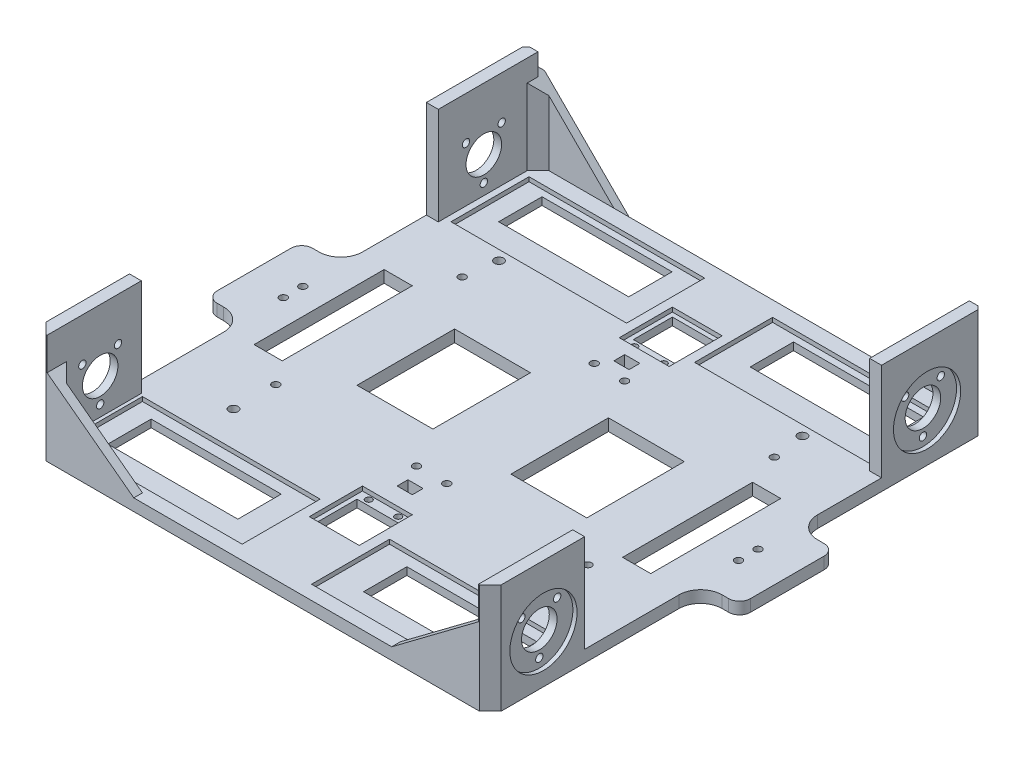
SolidWorks part; units mm, degrees
ref_plane "前视基准面" through (0, 0, 0) normal (0, 0, 1) x (1, 0, 0)
ref_plane "上视基准面" through (0, 0, 0) normal (0, 1, 0) x (1, 0, 0)
ref_plane "右视基准面" through (0, 0, 0) normal (1, 0, 0) x (0, 0, -1)
sketch "草图2" plane through (0, 0, 0) normal (0, 1, 0) x (1, 0, 0)
  line L1 (105, -109) -> (-105, -109)
  line L2 (130, -52) -> (130, 52)
  line L3 (105, 117.5) -> (-105, 117.5)
  line L4 (-130, -52) -> (-130, 52)
  line L5 (105, -94.9038) -> (-105, 94.9038) construction
  line L6 (105, 94.9038) -> (-105, -94.9038) construction
  line L9 (-130, 52) -> (-105, 52)
  line L10 (-105, 117.5) -> (-105, 52)
  line L13 (130, 52) -> (105, 52)
  line L14 (105, 117.5) -> (105, 52)
  line L17 (-130, -52) -> (-105, -52)
  line L18 (-105, -109) -> (-105, -52)
  line L21 (130, -52) -> (105, -52)
  line L22 (105, -109) -> (105, -52)
  line L23 (105, -109) -> (99.5, -109)
  line L24 (105, -109) -> (105, -74)
  line L25 (105, -74) -> (99.5, -74)
  line L26 (99.5, -109) -> (99.5, -74)
  line L27 (105, 117.5) -> (99.5, 117.5)
  line L28 (105, 117.5) -> (105, 82.5)
  line L29 (105, 82.5) -> (99.5, 82.5)
  line L30 (99.5, 117.5) -> (99.5, 82.5)
  point P0 (0, 0)
  dimension "D1" = 35
  dimension "D2" = 5.5
  dimension "D3" = 65.5
  dimension "D4" = 57
  dimension "D5" = 35
  dimension "D6" = 65.5
  dimension "D7" = 57
  dimension "D8" = 104
extrude "凸台-拉伸1" add sketch "草图2" along normal blind 5.5 contours L4 L9 L10 L3 L14 L13 L2 L21 L22 L1 L18 L17
sketch "草图5" plane through (0, 5.5, 0) normal (0, 1, 0) x (1, 0, 0)
  line L1 (105, -109) -> (99.5, -109)
  line L2 (105, -109) -> (105, -59.5)
  line L3 (105, -59.5) -> (99.5, -59.5)
  line L4 (99.5, -109) -> (99.5, -59.5)
  line L5 (105, 117.5) -> (99.5, 117.5)
  line L6 (105, 117.5) -> (105, 71.5)
  line L7 (105, 71.5) -> (99.5, 71.5)
  line L8 (99.5, 117.5) -> (99.5, 71.5)
extrude "凸台-拉伸2" add sketch "草图5" along normal blind 45
sketch "草图8" plane through (0, 0, -117.5) normal (0, 0, -1) x (-1, 0, 0)
  line L0 (-105, 45.921) -> (-59.079, 0)
  line L1 (-105, 50.5) -> (-105, 0) construction
  line L2 (-105, 0) -> (105, 0) construction
  line L3 (-59.079, 0) -> (-105, 0)
  line L4 (-105, 0) -> (-105, 45.921)
  dimension "D1" = 64.9422
  dimension "D2" = 45.921
  dimension "D3" = 45.921
extrude "凸台-拉伸4" add sketch "草图8" along normal blind 3.5
sketch "草图9" plane through (0, 5.5, 0) normal (0, 1, 0) x (1, 0, 0)
  line L0 (0, -109) -> (0, 117.5) construction
  line L3 (99.5, -109) -> (-105, -109) construction
  line L4 (64.579, 117.5) -> (-105, 117.5) construction
  circle A0 centre (-7, 50.9229) radius 1.7
  circle A1 centre (-71.9999, 55.0189) radius 1.7
  circle A2 centre (-71.9999, -30.9811) radius 1.7
  circle A3 centre (-7, -31.0771) radius 1.7
  circle A4 centre (7, -31.0771) radius 1.7
  circle A5 centre (71.9999, -30.9811) radius 1.7
  circle A6 centre (71.9999, 55.0189) radius 1.7
  circle A7 centre (7, 50.9229) radius 1.7
  dimension "D2" = 3.4
  dimension "D3" = 3.4
  dimension "D4" = 3.4
  dimension "D5" = 3.4
  dimension "D7" = 86
  dimension "D8" = 7
  dimension "D9" = 65
  dimension "D10" = 7
  dimension "D1" = 226.5
sketch "草图10" plane through (0, 5.5, 0) normal (0, 1, 0) x (1, 0, 0)
  line L1 (-105, 117.5) -> (-99.5, 117.5)
  line L2 (-105, 117.5) -> (-105, 71.5)
  line L3 (-105, 71.5) -> (-99.5, 71.5)
  line L4 (-99.5, 117.5) -> (-99.5, 71.5)
  line L5 (-105, -109) -> (-99.5, -109)
  line L6 (-105, -109) -> (-105, -59.5)
  line L7 (-105, -59.5) -> (-99.5, -59.5)
  line L8 (-99.5, -109) -> (-99.5, -59.5)
extrude "凸台-拉伸5" add sketch "草图10" along normal blind 45
sketch "草图11" plane through (0, 0, -117.5) normal (0, 0, -1) x (-1, 0, 0)
  line L0 (99.5, 50.5) -> (99.5, 5.5) construction
  line L1 (-64.579, 5.5) -> (99.5, 5.5) construction
  line L3 (-59.079, 0) -> (105, 0) construction
  line L4 (59, 0) -> (105, 46)
  line L6 (105, 46) -> (105, 0)
  line L7 (105, 50.5) -> (105, 0) construction
  line L8 (105, 0) -> (59, 0)
  point P0 (99.5, 40.5)
  point P5 (64.5, 5.5)
  dimension "D4" = 65.0538
  dimension "D5" = 46
  dimension "D6" = 46
extrude "凸台-拉伸6" add sketch "草图11" along normal blind 3.5 contours L4 L6 L8
sketch "草图15" plane through (0, 0, 109) normal (0, 0, 1) x (1, 0, 0)
  line L0 (-99.5, 40.5) -> (-59, 0)
  line L1 (105, 0) -> (-105, 0) construction
  line L2 (-59, 0) -> (-105, 46)
  point P8 (-105, 46)
  point P9 (-59, 0)
  dimension "D1" = 57.2756
  dimension "D2" = 65.0538
sketch "草图18" plane through (-105, 0, 0) normal (-1, 0, 0) x (0, 0, 1)
  line L0 (-117.5, 46) -> (-117.5, 5.5) construction
  line L1 (-71.5, 50.5) -> (-71.5, 5.5) construction
  line L2 (59.5, 50.5) -> (59.5, 5.5) construction
  line L4 (109, 5.5) -> (-117.5, 5.5) construction
  line L6 (109, 0) -> (52, 0) construction
  line L11 (52, 0) -> (109, 0)
  line L12 (109, 0) -> (109, 50.5)
  line L13 (109, 50.5) -> (59.5, 50.5)
  line L14 (59.5, 50.5) -> (59.5, 5.5)
  line L15 (59.5, 5.5) -> (52, 5.5)
  line L16 (52, 5.5) -> (52, 0)
  line L17 (52, 0) -> (109, 0)
  line L18 (109, 0) -> (109, 50.5)
  line L19 (109, 50.5) -> (59.5, 50.5)
  line L20 (59.5, 50.5) -> (59.5, 5.5)
  line L21 (59.5, 5.5) -> (52, 5.5)
  line L22 (52, 5.5) -> (52, 0)
  circle A1 centre (-92.5, 22) radius 8.2
  circle A3 centre (-100.725, 30.6) radius 1.7
  circle A4 centre (-84.275, 30.6) radius 1.7
  circle A5 centre (84.5, 22) radius 8.2
  circle A7 centre (76.275, 30.6) radius 1.7
  circle A8 centre (92.725, 30.6) radius 1.7
  circle A11 centre (84.5, 22) radius 8.2
  circle A12 centre (92.725, 30.6) radius 1.7
  circle A13 centre (76.275, 30.6) radius 1.7
  circle A15 centre (-92.5, 22) radius 8.2
  circle A16 centre (-84.275, 30.6) radius 1.7
  circle A17 centre (-100.725, 30.6) radius 1.7
  circle A19 centre (-92.5, 22) radius 15.5
  circle A20 centre (84.5, 22) radius 15.5
  circle A21 centre (84.5, 10.6) radius 1.7
  circle A22 centre (-92.5, 10.6) radius 1.7
  dimension "D2" = 16.4
  dimension "D5" = 0
  dimension "D7" = 3.4
  dimension "D9" = 3.4
  dimension "D12" = 8.2
  dimension "D14" = 20
  dimension "D16" = 3.4
  dimension "D19" = 3.4
  dimension "D21" = 16.4
  dimension "D22" = 3.4
  dimension "D23" = 3.4
  dimension "D25" = 16.4
  dimension "D26" = 3.4
  dimension "D27" = 3.4
  dimension "D31" = 31
  dimension "D32" = 31
  dimension "D33" = 22
  dimension "D6" = 3.4
  dimension "D10" = 3.4
  dimension "D1" = 40.5
  dimension "D4" = 21
  dimension "D8" = 11.9
  dimension "11.9" = 11.9
  dimension "D13" = 25
  dimension "D17" = 11.9
  dimension "D20" = 11.9
extrude "切除-拉伸2" cut sketch "草图18" against normal through all
sketch "草图20" plane through (0, 0, 0) normal (0, -1, 0) x (-1, 0, 0)
  line L0 (-130, 0) -> (130, 0)
  line L3 (-130, -52) -> (-130, 52) construction
  line L4 (130, -52) -> (130, 52) construction
  dimension "D1" = 260
sketch "草图24" plane through (0, 5.5, 0) normal (0, 1, 0) x (1, 0, 0)
  line L0 (-130, -52) -> (-130, 52) construction
  line L1 (-59, 121) -> (-105, 121) construction
  line L2 (59.079, 121) -> (105, 121) construction
  line L3 (130, -52) -> (130, 52) construction
  circle A0 centre (-72, -50.4834) radius 2.1
  circle A1 centre (-70, 70) radius 2.1
  circle A2 centre (72, -50.4834) radius 2.1
  circle A3 centre (70, 70) radius 2.1
  dimension "D1" = 4.2
  dimension "D2" = 4.2
  dimension "D3" = 4.2
  dimension "D4" = 4.2
  dimension "D5" = 58
  dimension "D6" = 60
  dimension "D7" = 60
  dimension "D9" = 51
  dimension "D10" = 51
  dimension "D11" = 120.5
  dimension "D12" = 120.5
  dimension "D8" = 58
sketch "草图55" plane through (0, 0, 0) normal (0, -1, 0) x (1, 0, 0)
  circle A0 centre (71.9999, -55.0189) radius 1.7
  circle A1 centre (7, -50.9229) radius 1.7
  circle A2 centre (-7, -50.9229) radius 1.7
  circle A3 centre (-71.9999, -55.0189) radius 1.7
  circle A4 centre (-71.9999, 30.9811) radius 1.7
  circle A5 centre (-7, 31.0771) radius 1.7
  circle A6 centre (7, 31.0771) radius 1.7
  circle A7 centre (71.9999, 30.9811) radius 1.7
  dimension "D1" = 3.4
  dimension "D2" = 3.4
  dimension "D3" = 3.4
  dimension "D4" = 3.4
  dimension "D5" = 3.4
  dimension "D6" = 3.4
  dimension "D7" = 3.4
  dimension "D8" = 3.4
extrude "切除-拉伸20" cut sketch "草图9" against normal blind 10 contours A6 | A5 | A4 | A7 | A0 | A3 | A2 | A1
fillet "圆角1" radius 1.5 8 edges at (-71.9999, 0, -53.3189) (-71.9999, 0, 32.6811) (-7, 0, 32.7771) (7, 0, 32.7771) (71.9999, 0, 32.6811) (71.9999, 0, -53.3189) (-7, 0, -49.2229) (7, 0, -49.2229) profile chamfer
extrude "切除-拉伸6" cut sketch "草图24" against normal blind 10
sketch "草图25" plane through (0, 5.5, 0) normal (0, 1, 0) x (1, 0, 0)
  line L0 (99.5, -109) -> (-99.5, -109) construction
  line L13 (-13.5, -94) -> (13.5, -94)
  line L14 (-13.5, -94) -> (-13.5, -89)
  line L15 (-13.5, -89) -> (13.5, -89)
  line L16 (13.5, -94) -> (13.5, -89)
  line L17 (-13.5, 102.5) -> (13.5, 102.5)
  line L18 (-13.5, 102.5) -> (-13.5, 107.5)
  line L19 (-13.5, 107.5) -> (13.5, 107.5)
  line L20 (13.5, 102.5) -> (13.5, 107.5)
  line L21 (64.579, 117.5) -> (-64.5, 117.5) construction
  line L23 (130, 0) -> (-130, 0) construction
  line L24 (0, 0) -> (130, 0) construction
  line L26 (0, -109) -> (0, 39.6584) construction
  line L27 (0, -109) -> (0, 117.5) construction
  point P24 (0, 0)
  dimension "D1" = 15
  dimension "D2" = 5
  dimension "D3" = 5
  dimension "D8" = 10
extrude "凸台-拉伸7" add sketch "草图25" along normal blind 34
sketch "草图27" plane through (0, 0, 94) normal (0, 0, 1) x (1, 0, 0)
  line L0 (-13.5, 5.5) -> (13.5, 5.5) construction
  line L1 (0, 39.5) -> (0, 4.5073) construction
  line L3 (-13.5, 39.5) -> (13.5, 39.5) construction
  circle A0 centre (0, 25.5) radius 9.6
  dimension "D1" = 19.2
  dimension "D2" = 20
  dimension "D3" = 34.9927
extrude "切除-拉伸11" cut sketch "草图27" against normal blind 34
sketch "草图35" plane through (0, 0, -107.5) normal (0, 0, -1) x (-1, 0, 0)
  line L0 (-13.5, 5.5) -> (13.5, 5.5) construction
  line L2 (0, 39.5) -> (0, 5.5856) construction
  line L3 (-13.5, 39.5) -> (13.5, 39.5) construction
  circle A0 centre (0.4008, 27.5) radius 9.6
  dimension "D1" = 19.2
  dimension "D2" = 22
  dimension "D3" = 33.9144
extrude "切除-拉伸12" cut sketch "草图35" against normal blind 34
sketch "草图43" plane through (0, 0, -107.5) normal (0, 0, -1) x (-1, 0, 0)
  line L0 (0, 39.5) -> (0, 5.5) construction
  line L3 (-13.5, 39.5) -> (13.5, 39.5) construction
  line L4 (-13.5, 5.5) -> (13.5, 5.5) construction
  dimension "D1" = 34
sketch "草图53" plane through (105, 0, 0) normal (1, 0, 0) x (0, 0, -1)
  circle A0 centre (-84.5, 22) radius 15.5
  circle A1 centre (92.5, 22) radius 15.5
  dimension "D1" = 31
  dimension "D2" = 31
extrude "切除-拉伸16" cut sketch "草图53" against normal blind 1.9
sketch "草图54" plane through (-105, 0, 0) normal (-1, 0, 0) x (0, 0, 1)
  circle A0 centre (-92.5, 22) radius 15.5
  circle A1 centre (84.5, 22) radius 15.5
  dimension "D1" = 31
  dimension "D2" = 31
extrude "切除-拉伸17" cut sketch "草图54" against normal blind 1.9
sketch "草图56" plane through (0, 5.5, 0) normal (0, 1, 0) x (1, 0, 0)
  line L19 (-130, -52) -> (-130, 52) construction
  line L20 (-105, 52) -> (-130, 52)
  line L21 (-105, 52) -> (-105, 32)
  line L22 (-105, 32) -> (-130, 32)
  line L23 (-130, 52) -> (-130, 32)
  line L24 (130, -52) -> (130, 52) construction
  line L25 (105, 52) -> (130, 52)
  line L26 (105, 52) -> (105, 32)
  line L27 (105, 32) -> (130, 32)
  line L28 (130, 52) -> (130, 32)
  line L30 (-130, -52) -> (-105, -52)
  line L31 (-130, -52) -> (-130, -12)
  line L32 (-130, -12) -> (-105, -12)
  line L33 (-105, -52) -> (-105, -12)
  line L34 (130, -52) -> (105, -52)
  line L35 (130, -52) -> (130, -12)
  line L36 (130, -12) -> (105, -12)
  line L37 (105, -52) -> (105, -12)
extrude "切除-拉伸21" cut sketch "草图56" against normal blind 10
sketch "草图61" plane through (0, 5.5, 0) normal (0, 1, 0) x (1, 0, 0)
sketch "草图63" plane through (0, 5.5, 0) normal (0, 1, 0) x (1, 0, 0)
  line L0 (-130, -12) -> (-130, 32) construction
  line L1 (-130, 32) -> (-105, 32) construction
  line L3 (105, 32) -> (130, 32) construction
  line L6 (130, -12) -> (130, 32) construction
  circle A0 centre (-105, 14.5) radius 1.7
  circle A1 centre (-105, 5.5) radius 1.7
  circle A2 centre (105, 14.5) radius 1.7
  circle A3 centre (105, 5.5) radius 1.7
  dimension "D1" = 25
  dimension "D4" = 26.5
  dimension "D2" = 17.5
  dimension "D3" = 9
  dimension "D5" = 25
sketch "草图64" plane through (0, 0, -102.5) normal (0, 0, 1) x (1, 0, 0)
  line L0 (-13.5, 39.5) -> (-13.5, 5.5) construction
  line L1 (13.5, 5.5) -> (9.5, 5.5)
  line L2 (13.5, 5.5) -> (13.5, 15.5)
  line L3 (13.5, 15.5) -> (9.5, 15.5)
  line L4 (9.5, 5.5) -> (9.5, 15.5)
  line L5 (-13.5, 15.5) -> (-9.5, 15.5)
  line L6 (-13.5, 15.5) -> (-13.5, 5.5)
  line L7 (-13.5, 5.5) -> (-9.5, 5.5)
  line L8 (-9.5, 15.5) -> (-9.5, 5.5)
  line L9 (-13.5, 5.5) -> (13.5, 5.5) construction
extrude "凸台-拉伸9" add sketch "草图64" along normal blind 10
sketch "草图65" plane through (13.5, 0, 0) normal (1, 0, 0) x (0, 0, -1)
  line L0 (103.5, 15.5) -> (92.5, 5.5)
  line L1 (92.5, 15.5) -> (102.5, 15.5) construction
  line L2 (92.5, 5.5) -> (92.5, 15.5)
  line L3 (92.5, 5.5) -> (92.5, 15.5) construction
  line L4 (92.5, 15.5) -> (103.5, 15.5)
extrude "切除-拉伸22" cut sketch "草图65" against normal blind 50
sketch "草图66" plane through (0, 0, 89) normal (0, 0, -1) x (-1, 0, 0)
  line L0 (-13.5, 39.5) -> (-13.5, 5.5) construction
  line L1 (-13.5, 15.5) -> (-9.5, 15.5)
  line L2 (-13.5, 15.5) -> (-13.5, 5.5)
  line L3 (-13.5, 5.5) -> (-9.5, 5.5)
  line L4 (-9.5, 15.5) -> (-9.5, 5.5)
  line L5 (-13.5, 5.5) -> (13.5, 5.5) construction
  line L7 (13.5, 5.5) -> (9.5, 5.5)
  line L8 (13.5, 5.5) -> (13.5, 15.5)
  line L9 (13.5, 15.5) -> (9.5, 15.5)
  line L10 (9.5, 5.5) -> (9.5, 15.5)
extrude "凸台-拉伸10" add sketch "草图66" along normal blind 10
sketch "草图67" plane through (-13.5, 0, 0) normal (-1, 0, 0) x (0, 0, 1)
  line L0 (89, 15.5) -> (79, 15.5)
  line L1 (79, 5.5) -> (79, 15.5) construction
  line L2 (79, 15.5) -> (89, 15.5) construction
  line L3 (79, 15.5) -> (79, 5.5)
  line L4 (79, 5.5) -> (89, 15.5)
extrude "切除-拉伸23" cut sketch "草图67" against normal blind 47
sketch "草图68" plane through (0, 5.5, 0) normal (0, 1, 0) x (1, 0, 0)
  line L0 (-130, -12) -> (-130, 32) construction
  line L1 (-53, 32.5) -> (-18, 32.5)
  line L2 (-53, 32.5) -> (-53, -12.5)
  line L3 (-53, -12.5) -> (-18, -12.5)
  line L4 (-18, 32.5) -> (-18, -12.5)
  line L5 (18, 32.5) -> (53, 32.5)
  line L6 (18, 32.5) -> (18, -12.5)
  line L7 (18, -12.5) -> (53, -12.5)
  line L8 (53, 32.5) -> (53, -12.5)
  line L9 (130, -12) -> (130, 32) construction
  line L11 (-130, 10) -> (130, 10) construction
  point P12 (-35.5, 32.5)
  dimension "D1" = 77
  dimension "D2" = 77
  dimension "D3" = 35
  dimension "D4" = 35
  dimension "D5" = 45
  dimension "D6" = 22.5
  dimension "D7" = 22.5
extrude "切除-拉伸24" cut sketch "草图68" against normal blind 10
sketch "草图69" plane through (0, 5.5, 0) normal (0, 1, 0) x (1, 0, 0)
  line L1 (9.5, 89.5) -> (-9.5, 89.5)
  line L2 (9.5, 89.5) -> (9.5, 71.5)
  line L3 (9.5, 71.5) -> (-9.5, 71.5)
  line L4 (-9.5, 89.5) -> (-9.5, 71.5)
  line L10 (99.5, -109) -> (-99.5, -109) construction
  line L11 (9.5, -56) -> (-9.5, -56)
  line L12 (9.5, -56) -> (9.5, -74)
  line L13 (9.5, -74) -> (-9.5, -74)
  line L14 (-9.5, -56) -> (-9.5, -74)
  line L19 (64.579, 117.5) -> (-64.5, 117.5) construction
  line L20 (-105, 71.5) -> (-105, 32) construction
  line L21 (105, -109) -> (105, -59.5) construction
  line L22 (29, -71.5) -> (89, -71.5)
  line L23 (29, -71.5) -> (29, -91.5)
  line L24 (29, -91.5) -> (89, -91.5)
  line L25 (89, -71.5) -> (89, -91.5)
  line L26 (-29, -91.5) -> (-89, -91.5)
  line L27 (-29, -91.5) -> (-29, -71.5)
  line L28 (-29, -71.5) -> (-89, -71.5)
  line L29 (-89, -91.5) -> (-89, -71.5)
  line L30 (-87.6519, 87.5) -> (-27.6519, 87.5)
  line L31 (-87.6519, 87.5) -> (-87.6519, 107.5)
  line L32 (-87.6519, 107.5) -> (-27.6519, 107.5)
  line L33 (-27.6519, 87.5) -> (-27.6519, 107.5)
  line L34 (28.3822, 107.5) -> (88.3822, 107.5)
  line L35 (28.3822, 107.5) -> (28.3822, 87.5)
  line L36 (28.3822, 87.5) -> (88.3822, 87.5)
  line L37 (88.3822, 107.5) -> (88.3822, 87.5)
  line L38 (-105, -59.5) -> (-105, -109) construction
  point P4 (0, 89.5)
  dimension "D1" = 105
  dimension "D2" = 16
  dimension "D3" = 35
  dimension "D4" = 28
  dimension "D5" = 16
  dimension "D6" = 17.5
  dimension "D7" = 10
extrude "切除-拉伸25" cut sketch "草图69" against normal blind 10
extrude "切除-拉伸26" cut sketch "草图63" against normal blind 19
sketch "草图73" plane through (0, 5.5, 0) normal (0, 1, 0) x (1, 0, 0)
  line L0 (-130, -12) -> (-130, 32) construction
  line L1 (-93, 40) -> (-80, 40)
  line L2 (-93, 40) -> (-93, -20)
  line L3 (-93, -20) -> (-80, -20)
  line L4 (-80, 40) -> (-80, -20)
  line L5 (77, 40) -> (90, 40)
  line L6 (77, 40) -> (77, -20)
  line L7 (77, -20) -> (90, -20)
  line L8 (90, 40) -> (90, -20)
  line L9 (130, -12) -> (130, 32) construction
  line L10 (-130, 10) -> (130, 10) construction
  dimension "D1" = 157
  dimension "D2" = 40
  dimension "D3" = 13
  dimension "D4" = 60
  dimension "D5" = 30
  dimension "D6" = 13
  dimension "D7" = 30
extrude "切除-拉伸27" cut sketch "草图73" against normal blind 10
fillet "圆角2" radius 5 1 edges at (-130, 2.75, -32)
fillet "圆角3" radius 5 1 edges at (130, 2.75, 12)
fillet "圆角4" radius 5 1 edges at (130, 2.75, -32)
fillet "圆角5" radius 10 1 edges at (105, 2.75, -32)
fillet "圆角6" radius 10 1 edges at (105, 2.75, 12)
fillet "圆角7" radius 10 1 edges at (-105, 2.75, 12)
fillet "圆角8" radius 5 1 edges at (-130, 2.75, 12)
fillet "圆角9" radius 10 1 edges at (-105, 2.75, -32)
sketch "草图81" plane through (99.5, 0, 0) normal (-1, 0, 0) x (0, 0, 1)
  line L1 (109, 5.5) -> (105, 5.5)
  line L2 (109, 5.5) -> (109, 35.5)
  line L3 (109, 35.5) -> (105, 35.5)
  line L4 (105, 5.5) -> (105, 35.5)
extrude "凸台-拉伸15" add sketch "草图81" along normal blind 40
sketch "草图82" plane through (-99.5, 0, 0) normal (1, 0, 0) x (0, 0, -1)
  line L1 (-109, 5.5) -> (-105, 5.5)
  line L2 (-109, 5.5) -> (-109, 35.5)
  line L3 (-109, 35.5) -> (-105, 35.5)
  line L4 (-105, 5.5) -> (-105, 35.5)
extrude "凸台-拉伸16" add sketch "草图82" along normal blind 40
sketch "草图83" plane through (0, 0, 109) normal (0, 0, 1) x (1, 0, 0)
  line L0 (-99.5, 35.5) -> (-59.5, 5.5)
  line L1 (-59.5, 5.5) -> (-59.5, 35.5)
  line L2 (-59.5, 35.5) -> (-99.5, 35.5)
  line L3 (59.5, 35.5) -> (99.5, 35.5)
  line L4 (99.5, 35.5) -> (59.5, 5.5)
  line L5 (59.5, 5.5) -> (59.5, 35.5)
extrude "切除-拉伸29" cut sketch "草图83" against normal blind 4
sketch "草图84" plane through (-105, 0, 0) normal (-1, 0, 0) x (0, 0, 1)
  line L0 (59.5, 50.5) -> (59.5, 5.5) construction
  line L1 (59.5, 5.5) -> (65.5, 5.5)
  line L2 (59.5, 5.5) -> (59.5, 50.5)
  line L3 (59.5, 50.5) -> (65.5, 50.5)
  line L4 (65.5, 5.5) -> (65.5, 50.5)
  line L5 (59.5, 50.5) -> (109, 50.5) construction
  circle A0 centre (84.5, 22) radius 8.2 construction
  dimension "D1" = 19
extrude "切除-拉伸30" cut sketch "草图84" against normal blind 5000
sketch "草图85" plane through (0, 5.5, 0) normal (0, 1, 0) x (1, 0, 0)
  line L0 (-9.5, 71.5) -> (9.5, 71.5) construction
  line L1 (9.5, -56) -> (-9.5, -56) construction
  line L2 (9.5, -74) -> (9.5, -56) construction
  line L3 (-9.5, 89.5) -> (-9.5, 71.5) construction
  line L4 (-3.5, 61.5) -> (3.5, 61.5)
  line L5 (-3.5, 61.5) -> (-3.5, 56.5)
  line L6 (-3.5, 56.5) -> (3.5, 56.5)
  line L7 (3.5, 61.5) -> (3.5, 56.5)
  line L8 (-3.5, -38.5) -> (3.5, -38.5)
  line L9 (-3.5, -38.5) -> (-3.5, -43.5)
  line L10 (-3.5, -43.5) -> (3.5, -43.5)
  line L11 (3.5, -38.5) -> (3.5, -43.5)
  line L13 (-9.5, -56) -> (-9.5, -74) construction
  circle A0 centre (-6.5941, 69) radius 1.5
  circle A1 centre (7, 69) radius 1.5
  circle A2 centre (7, -53.5) radius 1.5
  circle A3 centre (-6.5941, -53.5) radius 1.5
  point P22 (0, 61.5)
  point P25 (0, -43.5)
  dimension "D1" = 2.5
  dimension "D2" = 2.5
  dimension "D3" = 2.5
  dimension "D4" = 10
  dimension "D5" = 10
  dimension "D6" = 9.5
  dimension "D7" = 9.5
extrude "切除-拉伸31" cut sketch "草图85" against normal blind 10
chamfer "倒角3" distance 0.5 angle 45 2 edges at (7, 0, -67.5) (-6.5941, 0, -67.5)
chamfer "倒角6" distance 1.5 angle 45 3 edges at (70, 0, -67.9) (72, 0, 52.5834) (-72, 0, 52.5834)
chamfer "倒角7" distance 2 angle 45 1 edges at (-70, 0, -67.9)
chamfer "倒角8" distance 1 angle 45 4 edges at (105, 0, -12.8) (105, 0, -3.8) (-105, 0, -12.8) (-105, 0, -3.8)
chamfer "倒角9" distance 0.5 angle 45 2 edges at (-6.5941, 0, 55) (7, 0, 55)
sketch "草图86" plane through (0, 5.5, 0) normal (0, 1, 0) x (1, 0, 0)
  line L0 (-9.5, -74) -> (9.5, -74) construction
  line L1 (-11.5, 67) -> (11.5, 67)
  line L2 (-11.5, 67) -> (-11.5, 91.5)
  line L3 (-11.5, 91.5) -> (11.5, 91.5)
  line L4 (11.5, 67) -> (11.5, 91.5)
  line L17 (-11.5, -51.5) -> (11.5, -51.5)
  line L18 (-11.5, -51.5) -> (-11.5, -76)
  line L19 (-11.5, -76) -> (11.5, -76)
  line L20 (11.5, -51.5) -> (11.5, -76)
  line L25 (-9.5, -56) -> (-9.5, -74) construction
  line L26 (9.5, 89.5) -> (-9.5, 89.5) construction
  line L27 (9.5, 71.5) -> (9.5, 89.5) construction
  line L29 (-9.5, 89.5) -> (-9.5, 71.5) construction
  line L30 (9.5, -74) -> (9.5, -56) construction
  circle A1 centre (-6.5941, 69) radius 1.5 construction
  circle A2 centre (-6.5941, -53.5) radius 1.5 construction
  dimension "D1" = 2
  dimension "D2" = 2
  dimension "D3" = 2
  dimension "D4" = 2
  dimension "D5" = 2
  dimension "D6" = 2
  dimension "D7" = 2
  dimension "D8" = 2
extrude "切除-拉伸33" cut sketch "草图86" against normal blind 2
sketch "草图87" plane through (0, 5.5, 0) normal (0, 1, 0) x (1, 0, 0)
  line L0 (-125, 32) -> (-115, 32) construction
  line L1 (-123, 32) -> (-123, -12)
  line L2 (-115, -12) -> (-125, -12) construction
  line L3 (0.0395, 117.5) -> (0, -109) construction
  line L4 (64.579, 117.5) -> (-64.5, 117.5) construction
  line L5 (59.5, -109) -> (-59.5, -109) construction
  line L6 (-130, -7) -> (-130, 27) construction
  line L8 (123, 32) -> (123, -12)
  line L9 (115, 32) -> (125, 32) construction
  line L10 (125, -12) -> (115, -12) construction
  line L11 (130, -7) -> (130, 27) construction
  line L12 (-150.8479, 43.1233) -> (-123, 43.1233)
  line L13 (-150.8479, 43.1233) -> (-150.8479, -16.6597)
  line L14 (-150.8479, -16.6597) -> (-123, -16.6597)
  line L15 (-123, 43.1233) -> (-123, -16.6597)
  line L16 (123, 45.6946) -> (149.0313, 45.6946)
  line L17 (123, 45.6946) -> (123, -16.6597)
  line L18 (123, -16.6597) -> (149.0313, -16.6597)
  line L19 (149.0313, 45.6946) -> (149.0313, -16.6597)
  dimension "D1" = 7
  dimension "D2" = 7
extrude "切除-拉伸36" cut sketch "草图87" against normal blind 10 contours L15 L12 L13 L14 L1 | L19 L16 L17 L8 L18
fillet "圆角10" radius 5 4 edges at (123, 2.75, 12) (123, 2.75, -32) (-123, 2.75, 12) (-123, 2.75, -32)
chamfer "倒角10" distance 5 angle 45 2 edges at (0, 5.5, -102.5) (0, 5.5, 89)
chamfer "倒角11" distance 5 angle 45 8 edges at (105, 25.25, 109) (105, 22.9605, -121) (-105, 23, -121) (-105, 25.25, 109) (99.5, 20.5, 105) (-99.5, 20.5, 105) (-99.5, 23, -117.5) (99.5, 22.9605, -117.5)
sketch "草图88" plane through (0, 5.5, 0) normal (0, 1, 0) x (1, 0, 0)
  line L0 (0.0395, 117.5) -> (0.0395, 0) construction
  line L1 (-96.6519, 110.5) -> (-15.6519, 110.5)
  line L2 (-96.6519, 110.5) -> (-96.6519, 74.5)
  line L3 (-96.6519, 74.5) -> (-15.6519, 74.5)
  line L4 (-15.6519, 110.5) -> (-15.6519, 74.5)
  line L5 (64.579, 117.5) -> (-64.5, 117.5) construction
  line L6 (-64.5, 117.5) -> (-94.5, 117.5) construction
  line L7 (0, -109) -> (0, -27.8123) construction
  line L8 (-87.6519, 87.5) -> (-27.6519, 87.5) construction
  line L9 (-27.6519, 87.5) -> (-27.6519, 107.5) construction
  line L10 (-87.6519, 107.5) -> (-87.6519, 87.5) construction
  line L11 (15.7309, 110.5) -> (15.7309, 74.5)
  line L12 (96.7309, 74.5) -> (15.7309, 74.5)
  line L13 (96.7309, 110.5) -> (96.7309, 74.5)
  line L14 (96.7309, 110.5) -> (15.7309, 110.5)
  line L17 (59.5, -109) -> (-59.5, -109) construction
  line L18 (-89, -71.5) -> (-89, -91.5) construction
  line L19 (-98, -66.5) -> (-16, -66.5)
  line L20 (-98, -66.5) -> (-98, -102.5)
  line L21 (-98, -102.5) -> (-16, -102.5)
  line L22 (-16, -66.5) -> (-16, -102.5)
  line L27 (-29, -71.5) -> (-89, -71.5) construction
  line L28 (-29, -91.5) -> (-29, -71.5) construction
  line L30 (-89, -91.5) -> (-29, -91.5) construction
  line L31 (16, -66.5) -> (16, -102.5)
  line L32 (98, -102.5) -> (16, -102.5)
  line L33 (98, -66.5) -> (98, -102.5)
  line L34 (98, -66.5) -> (16, -66.5)
  dimension "D1" = 7
  dimension "D2" = 13
  dimension "D3" = 12
  dimension "D4" = 9
  dimension "D5" = 9
  dimension "D6" = 5
  dimension "D7" = 13
  dimension "D8" = 11
extrude "切除-拉伸37" cut sketch "草图88" against normal blind 2
sketch "草图90" plane through (0, 0, 109) normal (0, 0, 1) x (1, 0, 0)
  line L0 (59.5, 5.5) -> (-59.5, 5.5) construction
  line L1 (-18.8628, 5.5) -> (25.1581, 5.5)
  line L2 (-18.8628, 5.5) -> (-18.8628, 49.4252)
  line L3 (-18.8628, 49.4252) -> (25.1581, 49.4252)
  line L4 (25.1581, 5.5) -> (25.1581, 49.4252)
extrude "切除-拉伸39" cut sketch "草图90" against normal blind 300
